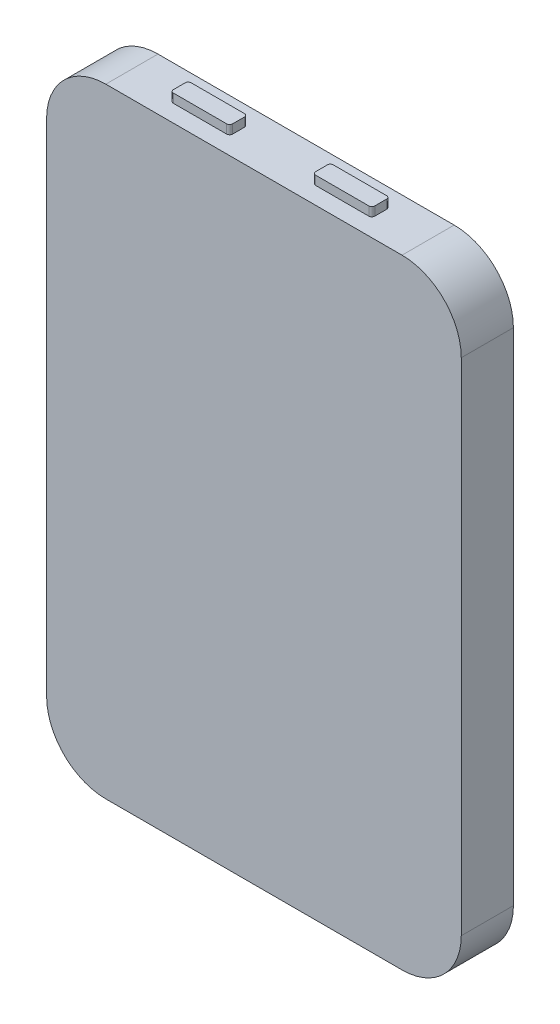
SolidWorks part; units mm, degrees
ref_plane "前基準面" through (0, 0, 0) normal (0, 0, 1) x (1, 0, 0)
ref_plane "上基準面" through (0, 0, 0) normal (0, 1, 0) x (1, 0, 0)
ref_plane "右基準面" through (0, 0, 0) normal (1, 0, 0) x (0, 0, -1)
sketch "草圖1" plane through (0, 0, 0) normal (0, 0, 1) x (1, 0, 0)
  line L5 (-25, -52.25) -> (25, -52.25)
  line L6 (-35, -42.25) -> (-35, 42.25)
  line L7 (-25, 52.25) -> (25, 52.25)
  line L8 (35, -42.25) -> (35, 42.25)
  line L9 (-35, -52.25) -> (35, 52.25) construction
  line L10 (-35, 52.25) -> (35, -52.25) construction
  arc A0 (35, 42.25) -> (25, 52.25) centre (25, 42.25) ccw
  arc A1 (25, -52.25) -> (35, -42.25) centre (25, -42.25) ccw
  arc A2 (-25, -52.25) -> (-35, -42.25) centre (-25, -42.25) cw
  arc A3 (-35, 42.25) -> (-25, 52.25) centre (-25, 42.25) cw
  point P0 (0, 0)
  dimension "D3" = 10
  dimension "D1" = 70
  dimension "D2" = 104.5
extrude "填料-伸長1" add sketch "草圖1" along normal blind 8.8
sketch "草圖2" plane through (0, 52.25, 0) normal (0, 1, 0) x (1, 0, 0)
  line L0 (-27.1548, -4.4) -> (32.5328, -4.4) construction
  line L1 (-35, -8.8) -> (-35, 0) construction
  line L2 (-16.5, -5.9) -> (-7.5, -5.9)
  line L3 (-17, -5.4) -> (-17, -3.4)
  line L4 (25, 0) -> (-25, 0)
  line L5 (-25, 0) -> (-25, -8.8)
  line L6 (-25, -8.8) -> (25, -8.8)
  line L7 (25, -8.8) -> (25, 0)
  line L8 (25, 0) -> (-25, 0) construction
  line L9 (-25, 0) -> (-25, -8.8) construction
  line L10 (-25, -8.8) -> (25, -8.8) construction
  line L11 (25, -8.8) -> (25, 0) construction
  line L12 (-16.5, -2.9) -> (-7.5, -2.9)
  line L13 (-7, -5.4) -> (-7, -3.4)
  line L14 (-17, -5.9) -> (-7, -2.9) construction
  line L15 (-17, -2.9) -> (-7, -5.9) construction
  line L16 (7.5, -5.9) -> (16.5, -5.9)
  line L17 (7, -5.4) -> (7, -3.4)
  line L18 (7.5, -2.9) -> (16.5, -2.9)
  line L19 (17, -5.4) -> (17, -3.4)
  line L20 (7, -5.9) -> (17, -2.9) construction
  line L21 (7, -2.9) -> (17, -5.9) construction
  arc A0 (16.5, -5.9) -> (17, -5.4) centre (16.5, -5.4) ccw
  arc A1 (17, -3.4) -> (16.5, -2.9) centre (16.5, -3.4) ccw
  arc A2 (7, -5.4) -> (7.5, -5.9) centre (7.5, -5.4) ccw
  arc A3 (7, -3.4) -> (7.5, -2.9) centre (7.5, -3.4) cw
  arc A4 (-7, -3.4) -> (-7.5, -2.9) centre (-7.5, -3.4) ccw
  arc A5 (-7.5, -5.9) -> (-7, -5.4) centre (-7.5, -5.4) ccw
  arc A6 (-17, -5.4) -> (-16.5, -5.9) centre (-16.5, -5.4) ccw
  arc A7 (-17, -3.4) -> (-16.5, -2.9) centre (-16.5, -3.4) cw
  point P6 (-12, -4.4)
  point P11 (12, -4.4)
  dimension "D8" = 0.5
  dimension "D2" = 18
  dimension "D3" = 34
  dimension "D4" = 10
  dimension "D5" = 10
  dimension "D6" = 3
  dimension "D7" = 3
  dimension "D1" = 0
extrude "填料-伸長2" add sketch "草圖2" along normal blind 1.5
sketch "草圖3" plane through (0, 0, 0) normal (0, 0, -1) x (-1, 0, 0)
  line L0 (0, 63.3307) -> (0, -88.6264) construction
  line L1 (-14.0369, 48.3707) -> (18.2971, 48.3707) construction
  circle A0 centre (0, 48.3707) radius 0.5
  circle A1 centre (-2, 48.3707) radius 0.5027
  circle A2 centre (4, 48.3707) radius 0.5
  circle A3 centre (2, 48.3707) radius 0.5027
  circle A4 centre (-4, 48.3707) radius 0.5027
  dimension "D1" = 1
  dimension "D2" = 2
  dimension "D3" = 2
  dimension "D4" = 2
extrude "除料-伸長1" cut sketch "草圖3" against normal blind 0.1
